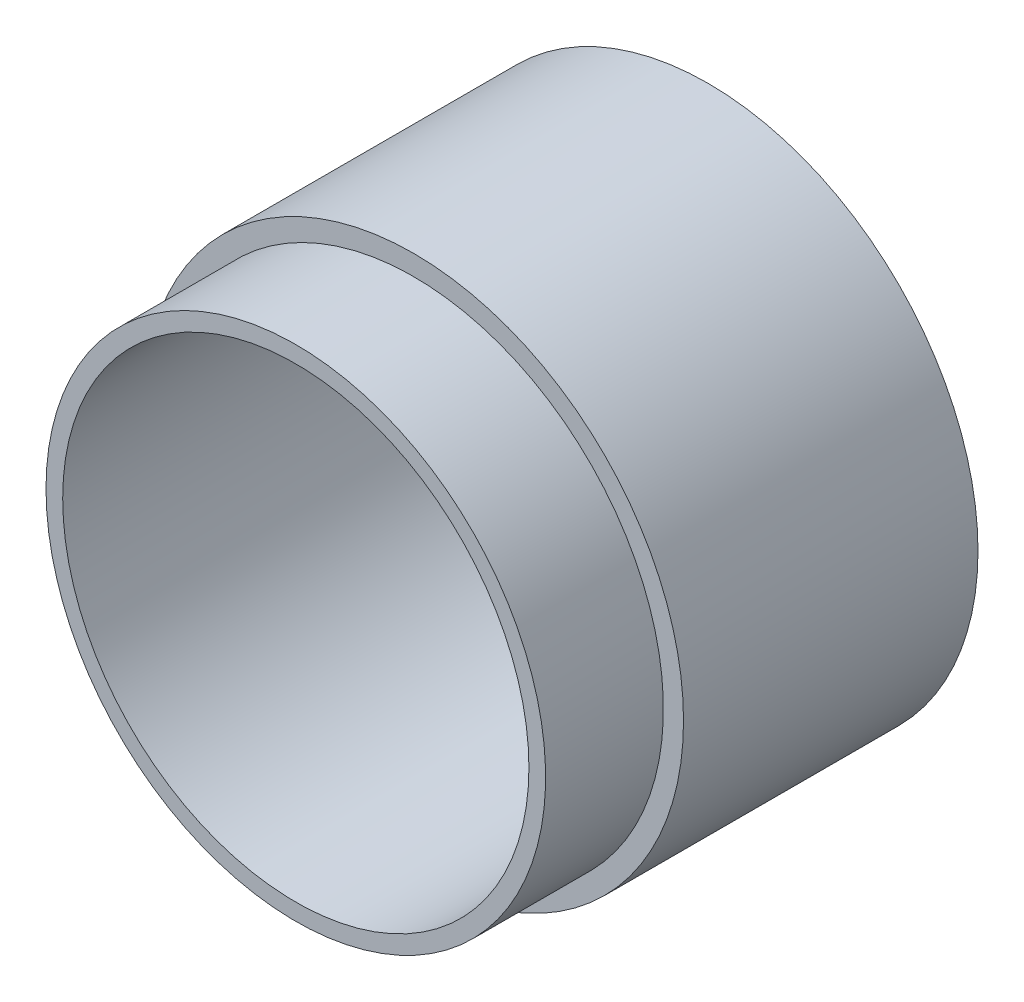
SolidWorks part; units mm, degrees
ref_plane "Front Plane" through (0, 0, 0) normal (0, 0, 1) x (1, 0, 0)
ref_plane "Top Plane" through (0, 0, 0) normal (0, 1, 0) x (1, 0, 0)
ref_plane "Right Plane" through (0, 0, 0) normal (1, 0, 0) x (0, 0, -1)
sketch "Sketch1" plane through (0, 0, 0) normal (0, 0, 1) x (1, 0, 0)
  circle A0 centre (0, 0) radius 12.065
  circle A1 centre (0, 0) radius 13.97
  dimension "D1" = 24.13
  dimension "D2" = 27.94
extrude "Boss-Extrude1" add sketch "Sketch1" along normal blind 15.24
sketch "Sketch2" plane through (0, 0, 0) normal (0, 0, -1) x (-1, 0, 0)
  circle A0 centre (0, 0) radius 13.97
  circle A1 centre (0, 0) radius 3.175
  dimension "D1" = 27.94
  dimension "D2" = 6.35
extrude "Boss-Extrude2" add sketch "Sketch2" against normal blind 1.27
sketch "Sketch3" plane through (0, 0, 15.24) normal (0, 0, 1) x (1, 0, 0)
  circle A0 centre (0, 0) radius 12.9286
  circle A1 centre (0, 0) radius 12.065
  dimension "D1" = 25.8572
  dimension "D2" = 24.13
extrude "Boss-Extrude3" add sketch "Sketch3" along normal blind 6.096
